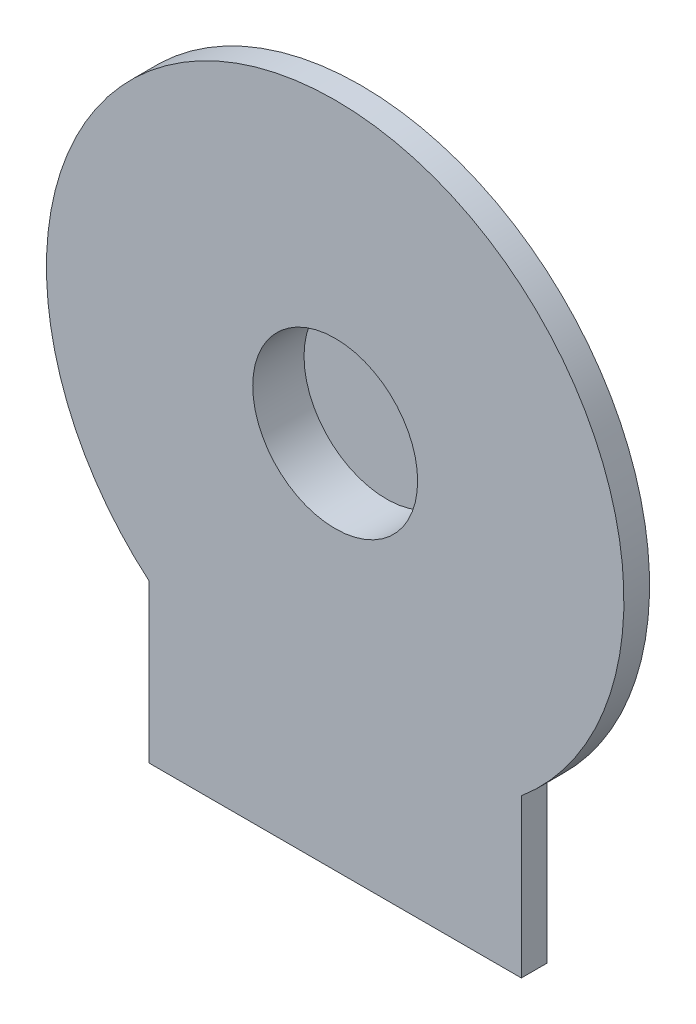
SolidWorks part; units mm, degrees
ref_plane "Front Plane" through (0, 0, 0) normal (0, 0, 1) x (1, 0, 0)
ref_plane "Top Plane" through (0, 0, 0) normal (0, 1, 0) x (1, 0, 0)
ref_plane "Right Plane" through (0, 0, 0) normal (1, 0, 0) x (0, 0, -1)
sketch "Sketch1" plane through (0, 0, 0) normal (0, 0, 1) x (1, 0, 0)
  line L0 (0, 0) -> (0, -73.8)
  line L1 (0, -73.8) -> (-36.3, -73.8)
  line L2 (-36.3, -73.8) -> (36.3, -73.8)
  line L3 (0, -73.8) -> (36.3, -73.8)
  line L4 (0, -73.8) -> (36.3, -73.8)
  line L5 (0, -32.2794) -> (36.3, -32.2794)
  line L6 (36.3, -32.2794) -> (-36.3, -32.2794)
  line L7 (-36.3, -32.2794) -> (-36.3, -72.6973)
  line L8 (0, -40.1542) -> (36.3, -40.1542)
  line L9 (36.3, -32.2794) -> (36.3, -73.8)
  line L10 (-36.3, -73.8) -> (-36.3, -32.2794)
  circle A0 centre (0, 0) radius 56.3
  dimension "D1" = 112.6
  dimension "D2" = 73.8
  dimension "D3" = 72.6
extrude "Boss-Extrude1" add sketch "Sketch1" along normal blind 5
sketch "Sketch2" plane through (0, 0, 0) normal (0, 0, -1) x (-1, 0, 0)
  circle A0 centre (0, 0) radius 16.075
  dimension "D1" = 32.15
extrude "Cut-Extrude1" cut sketch "Sketch2" against normal blind 33
sketch "Sketch3" plane through (0, 0, 0) normal (0, 0, -1) x (-1, 0, 0)
  circle A0 centre (0, 0) radius 16.075
  circle A1 centre (0, 0) radius 21.075
  dimension "D1" = 5
extrude "Boss-Extrude2" add sketch "Sketch3" along normal blind 5
sketch "Sketch4" plane through (0, 0, -5) normal (0, 0, -1) x (-1, 0, 0)
  circle A0 centre (0, 0) radius 21.075
extrude "Boss-Extrude3" add sketch "Sketch4" along normal blind 3
fillet "Fillet1" radius 7 1 edges at (21.075, 0, 0)
fillet "Fillet2" radius 7 1 edges at (-21.075, 0, -8)
